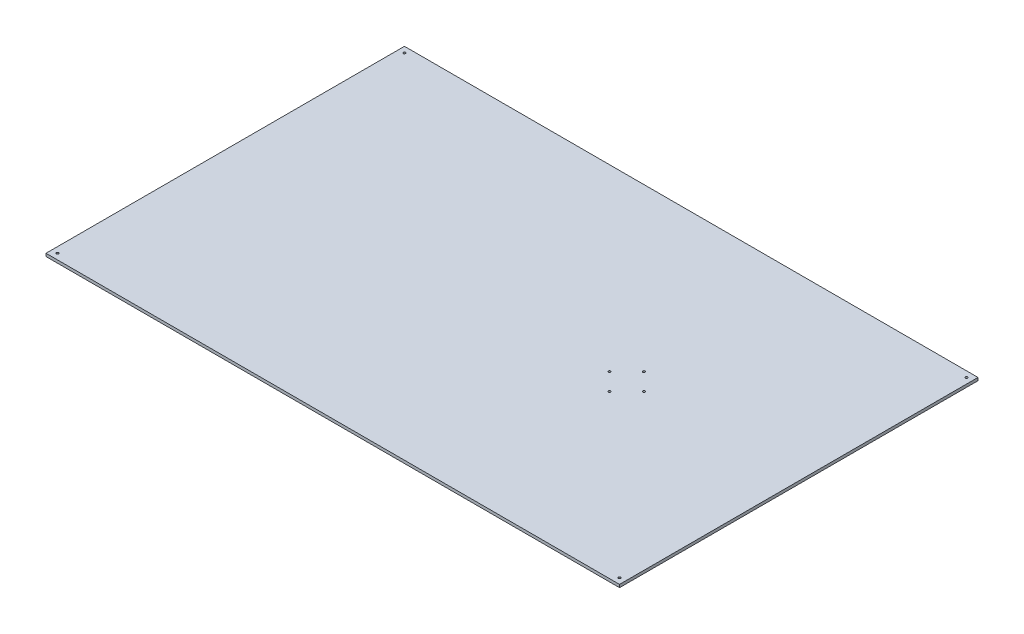
SolidWorks part; units mm, degrees
ref_plane "前视基准面" through (0, 0, 0) normal (0, 0, 1) x (1, 0, 0)
ref_plane "上视基准面" through (0, 0, 0) normal (0, 1, 0) x (1, 0, 0)
ref_plane "右视基准面" through (0, 0, 0) normal (1, 0, 0) x (0, 0, -1)
sketch "草图2" plane through (0, 0, 0) normal (0, 1, 0) x (1, 0, 0)
  line L0 (0, 863.8843) -> (0, -975.072) construction
  line L1 (-1426.8019, 0) -> (1553.6216, 0) construction
  line L2 (-1000, 625) -> (1000, 625)
  line L3 (-1000, -625) -> (1000, -625)
  line L4 (-1000, 625) -> (-1000, -625)
  line L5 (1000, 625) -> (1000, -625)
  line L6 (400, 163.4279) -> (400, -180.4687) construction
  circle A1 centre (400, 0) radius 60
  dimension "D1" = 600
  dimension "D3" = 2000
  dimension "D4" = 1250
extrude "凸台-拉伸1" add sketch "草图2" along normal blind 10 contours L4 L3 L5 L2
sketch "草图3" plane through (0, 10, 0) normal (0, 1, 0) x (1, 0, 0)
  line L0 (-1000, 625) -> (1000, 625) construction
  line L1 (-980, 605) -> (980, 605)
  line L2 (-980, 605) -> (-980, -605)
  line L3 (-980, -605) -> (980, -605)
  line L4 (980, 605) -> (980, -605)
  line L5 (-1000, 625) -> (-1000, -625) construction
  line L6 (-1000, -625) -> (1000, -625) construction
  line L7 (1000, 625) -> (1000, -625) construction
  dimension "D1" = 20
  dimension "D2" = 20
  dimension "D3" = 20
  dimension "D4" = 20
hole_wizard "大小mm 暗销孔1" positions "3D草图1" profile "草图4" hole size "Ø8.0" standard "ISO"
sketch3d "3D草图1"
  point P0 (-980, 10, -605)
  point P3 (980, 10, -605)
  point P6 (980, 10, 605)
  point P9 (-980, 10, 605)
sketch "草图4" plane through (-980, 10, -605) normal (1, 0, 0) x (0, 0, 1)
  line L0 (0, 0) -> (0, 22.4034)
  line L1 (0, 22.4034) -> (4, 20)
  line L2 (4, 20) -> (4, 0)
  line L5 (4, 0) -> (0, 0)
  line L10 (0, 22.4034) -> (-4, 20) construction
  line L11 (0, -6.35) -> (0, 107.95) construction
  dimension "孔直径" = 8
  dimension "孔深度" = 20
  dimension "导头角度" = 118
sketch "草图5" plane through (0, 10, 0) normal (0, 1, 0) x (1, 0, 0)
  line L0 (-1277.4468, 0) -> (1241.3671, 0) construction
  line L1 (400, 279.6177) -> (400, -245.7929) construction
  line L2 (1000, 625) -> (1000, -625) construction
  circle A0 centre (400, 0) radius 60
  dimension "D1" = 600
hole_wizard "大小mm 暗销孔2" positions "3D草图2" profile "草图6" hole size "Ø8.0" standard "ISO"
sketch3d "3D草图2"
  line L0 (400, 10, -279.6177) -> (400, 10, 245.7929) construction
  line L1 (-1277.4468, 10, 0) -> (1241.3671, 10, 0) construction
  circle A0 centre (400, 10, 0) radius 60 construction
  point P0 (400, 10, -60)
  point P4 (400, 70, 0)
  point P7 (340, 10, 0)
  point P11 (400, 10, 60)
  point P13 (460, 10, 0)
sketch "草图6" plane through (400, 10, -60) normal (1, 0, 0) x (0, 0, 1)
  line L0 (0, 0) -> (0, 22.4034)
  line L1 (0, 22.4034) -> (4, 20)
  line L2 (4, 20) -> (4, 0)
  line L5 (4, 0) -> (0, 0)
  line L10 (0, 22.4034) -> (-4, 20) construction
  line L11 (0, -6.35) -> (0, 107.95) construction
  dimension "孔直径" = 8
  dimension "孔深度" = 20
  dimension "导头角度" = 118
